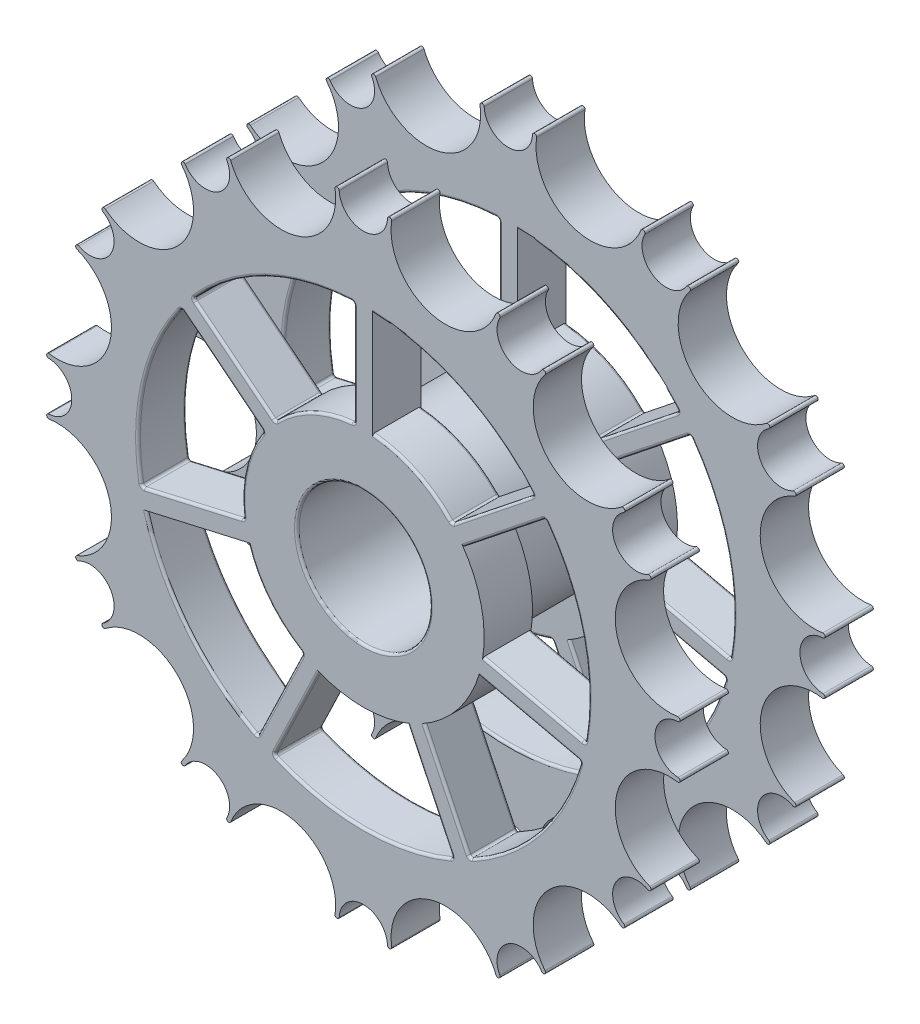
SolidWorks part; units mm, degrees
ref_plane "Front Plane" through (0, 0, 0) normal (0, 0, 1) x (1, 0, 0)
ref_plane "Top Plane" through (0, 0, 0) normal (0, 1, 0) x (1, 0, 0)
ref_plane "Right Plane" through (0, 0, 0) normal (1, 0, 0) x (0, 0, -1)
sketch "Sketch2" plane through (0, 0, 0) normal (0, 0, 1) x (1, 0, 0)
  line L0 (-169.1, 0) -> (169.1, 0) construction
  line L1 (169.1, 0) -> (0, 0) construction
  line L2 (-103.7648, 113.1639) -> (-169.1, 130.6704) construction
  line L3 (-234.4352, -113.1639) -> (-169.1, -130.6704) construction
  line L4 (-169.1, -130.6704) -> (-103.7648, -113.1639) construction
  line L5 (-103.7648, -113.1639) -> (-55.9361, -65.3352) construction
  line L6 (-55.9361, -65.3352) -> (-38.4296, 0) construction
  line L7 (-38.4296, 0) -> (-55.9361, 65.3352) construction
  line L8 (-55.9361, 65.3352) -> (-103.7648, 113.1639) construction
  line L9 (-169.1, 130.6704) -> (-234.4352, 113.1639) construction
  line L10 (-234.4352, 113.1639) -> (-282.2639, 65.3352) construction
  line L11 (-282.2639, 65.3352) -> (-299.7704, 0) construction
  line L12 (-299.7704, 0) -> (-282.2639, -65.3352) construction
  line L13 (-282.2639, -65.3352) -> (-234.4352, -113.1639) construction
  line L14 (-169.1, 130.6704) -> (169.1, 130.6704) construction
  line L15 (234.4352, -113.1639) -> (282.2639, -65.3352) construction
  line L16 (282.2639, -65.3352) -> (299.7704, 0) construction
  line L17 (299.7704, 0) -> (282.2639, 65.3352) construction
  line L18 (282.2639, 65.3352) -> (234.4352, 113.1639) construction
  line L19 (234.4352, 113.1639) -> (169.1, 130.6704) construction
  line L20 (169.1, 130.6704) -> (103.7648, 113.1639) construction
  line L21 (103.7648, 113.1639) -> (55.9361, 65.3352) construction
  line L22 (55.9361, 65.3352) -> (38.4296, 0) construction
  line L23 (38.4296, 0) -> (55.9361, -65.3352) construction
  line L24 (55.9361, -65.3352) -> (103.7648, -113.1639) construction
  line L25 (103.7648, -113.1639) -> (169.1, -130.6704) construction
  line L26 (169.1, -130.6704) -> (234.4352, -113.1639) construction
  line L27 (-169.1, -130.6704) -> (169.1, -130.6704) construction
  line L28 (-201.7676, 121.9172) -> (-203.0617, 126.7468) construction
  line L29 (-169.1, 130.6704) -> (-169.1, 0) construction
  line L30 (-169.1, 0) -> (-234.4352, 113.1639) construction
  circle A0 centre (-169.1, 0) radius 126.218 construction
  circle A1 centre (169.1, 0) radius 126.218 construction
  arc A2 (-169.1, 130.6704) -> (-169.1, -130.6704) centre (-169.1, 0) ccw construction
  arc A3 (169.1, 130.6704) -> (169.1, -130.6704) centre (169.1, 0) cw construction
  arc A4 (-179.0914, 130.2547) -> (-169.1, 120.6704) centre (-169.1, 130.6704) ccw
  arc A6 (-224.0026, 118.5171) -> (-180.8115, 130.0902) centre (-203.0617, 126.7468) ccw
  arc A7 (-179.0914, 130.2547) -> (-180.8115, 130.0902) centre (-179.9559, 130.2187) ccw
  arc A8 (-224.0026, 118.5171) -> (-225.5746, 117.7996) centre (-224.8079, 118.2006) ccw
  arc A9 (-229.4352, 104.5037) -> (-225.5746, 117.7996) centre (-234.4352, 113.1639) ccw
  arc A10 (-157.3885, 130.0902) -> (-114.1974, 118.5171) centre (-135.1383, 126.7468) ccw
  arc A11 (-112.6254, 117.7996) -> (-108.7648, 104.5037) centre (-103.7648, 113.1639) ccw
  arc A12 (-169.1, 120.6704) -> (-159.1086, 130.2547) centre (-169.1, 130.6704) ccw
  arc A13 (-157.3885, 130.0902) -> (-159.1086, 130.2547) centre (-158.2441, 130.2187) ccw
  arc A14 (-112.6254, 117.7996) -> (-114.1974, 118.5171) centre (-113.3921, 118.2006) ccw
  arc A15 (-93.9125, 106.8056) -> (-62.2944, 75.1875) centre (-76.3149, 92.7851) ccw
  arc A16 (-61.2918, 73.7801) -> (-64.5963, 60.3352) centre (-55.9361, 65.3352) ccw
  arc A17 (-108.7648, 104.5037) -> (-95.3199, 107.8082) centre (-103.7648, 113.1639) ccw
  arc A18 (-93.9125, 106.8056) -> (-95.3199, 107.8082) centre (-94.5892, 107.3448) ccw
  arc A19 (-61.2918, 73.7801) -> (-62.2944, 75.1875) centre (-61.7552, 74.5108) ccw
  arc A20 (-50.5829, 54.9026) -> (-39.0098, 11.7115) centre (-42.3532, 33.9617) ccw
  arc A21 (-38.8453, 9.9914) -> (-48.4296, 0) centre (-38.4296, 0) ccw
  arc A22 (-64.5963, 60.3352) -> (-51.3004, 56.4746) centre (-55.9361, 65.3352) ccw
  arc A23 (-50.5829, 54.9026) -> (-51.3004, 56.4746) centre (-50.8994, 55.7079) ccw
  arc A24 (-38.8453, 9.9914) -> (-39.0098, 11.7115) centre (-38.8813, 10.8559) ccw
  arc A25 (-39.0098, -11.7115) -> (-50.5829, -54.9026) centre (-42.3532, -33.9617) ccw
  arc A26 (-51.3004, -56.4746) -> (-64.5963, -60.3352) centre (-55.9361, -65.3352) ccw
  arc A27 (-48.4296, 0) -> (-38.8453, -9.9914) centre (-38.4296, 0) ccw
  arc A28 (-39.0098, -11.7115) -> (-38.8453, -9.9914) centre (-38.8813, -10.8559) ccw
  arc A29 (-51.3004, -56.4746) -> (-50.5829, -54.9026) centre (-50.8994, -55.7079) ccw
  arc A30 (-62.2944, -75.1875) -> (-93.9125, -106.8056) centre (-76.3149, -92.7851) ccw
  arc A31 (-95.3199, -107.8082) -> (-108.7648, -104.5037) centre (-103.7648, -113.1639) ccw
  arc A32 (-64.5963, -60.3352) -> (-61.2918, -73.7801) centre (-55.9361, -65.3352) ccw
  arc A33 (-62.2944, -75.1875) -> (-61.2918, -73.7801) centre (-61.7552, -74.5108) ccw
  arc A34 (-95.3199, -107.8082) -> (-93.9125, -106.8056) centre (-94.5892, -107.3448) ccw
  arc A35 (-114.1974, -118.5171) -> (-157.3885, -130.0902) centre (-135.1383, -126.7468) ccw
  arc A36 (-159.1086, -130.2547) -> (-169.1, -120.6704) centre (-169.1, -130.6704) ccw
  arc A37 (-108.7648, -104.5037) -> (-112.6254, -117.7996) centre (-103.7648, -113.1639) ccw
  arc A38 (-114.1974, -118.5171) -> (-112.6254, -117.7996) centre (-113.3921, -118.2006) ccw
  arc A39 (-159.1086, -130.2547) -> (-157.3885, -130.0902) centre (-158.2441, -130.2187) ccw
  arc A40 (-180.8115, -130.0902) -> (-224.0026, -118.5171) centre (-203.0617, -126.7468) ccw
  arc A41 (-225.5746, -117.7996) -> (-229.4352, -104.5037) centre (-234.4352, -113.1639) ccw
  arc A42 (-169.1, -120.6704) -> (-179.0914, -130.2547) centre (-169.1, -130.6704) ccw
  arc A43 (-180.8115, -130.0902) -> (-179.0914, -130.2547) centre (-179.9559, -130.2187) ccw
  arc A44 (-225.5746, -117.7996) -> (-224.0026, -118.5171) centre (-224.8079, -118.2006) ccw
  arc A45 (-244.2875, -106.8056) -> (-275.9056, -75.1875) centre (-261.8851, -92.7851) ccw
  arc A46 (-276.9082, -73.7801) -> (-273.6037, -60.3352) centre (-282.2639, -65.3352) ccw
  arc A47 (-229.4352, -104.5037) -> (-242.8801, -107.8082) centre (-234.4352, -113.1639) ccw
  arc A48 (-244.2875, -106.8056) -> (-242.8801, -107.8082) centre (-243.6108, -107.3448) ccw
  arc A49 (-276.9082, -73.7801) -> (-275.9056, -75.1875) centre (-276.4448, -74.5108) ccw
  arc A50 (-287.6171, -54.9026) -> (-299.1902, -11.7115) centre (-295.8468, -33.9617) ccw
  arc A51 (-299.3547, -9.9914) -> (-289.7704, 0) centre (-299.7704, 0) ccw
  arc A52 (-273.6037, -60.3352) -> (-286.8996, -56.4746) centre (-282.2639, -65.3352) ccw
  arc A53 (-287.6171, -54.9026) -> (-286.8996, -56.4746) centre (-287.3006, -55.7079) ccw
  arc A54 (-299.3547, -9.9914) -> (-299.1902, -11.7115) centre (-299.3187, -10.8559) ccw
  arc A55 (-299.1902, 11.7115) -> (-287.6171, 54.9026) centre (-295.8468, 33.9617) ccw
  arc A56 (-286.8996, 56.4746) -> (-273.6037, 60.3352) centre (-282.2639, 65.3352) ccw
  arc A57 (-289.7704, 0) -> (-299.3547, 9.9914) centre (-299.7704, 0) ccw
  arc A58 (-299.1902, 11.7115) -> (-299.3547, 9.9914) centre (-299.3187, 10.8559) ccw
  arc A59 (-286.8996, 56.4746) -> (-287.6171, 54.9026) centre (-287.3006, 55.7079) ccw
  arc A60 (-275.9056, 75.1875) -> (-244.2875, 106.8056) centre (-261.8851, 92.7851) ccw
  arc A61 (-242.8801, 107.8082) -> (-229.4352, 104.5037) centre (-234.4352, 113.1639) ccw
  arc A62 (-273.6037, 60.3352) -> (-276.9082, 73.7801) centre (-282.2639, 65.3352) ccw
  arc A63 (-275.9056, 75.1875) -> (-276.9082, 73.7801) centre (-276.4448, 74.5108) ccw
  arc A64 (-242.8801, 107.8082) -> (-244.2875, 106.8056) centre (-243.6108, 107.3448) ccw
  point P214 (-169.1, 0)
  dimension "D2" = 12
  dimension "D4" = 45
  dimension "D6" = 10
  dimension "D1" = 338.2
  dimension "D3" = 67.64
  dimension "D5" = 5
extrude "Boss-Extrude1" add sketch "Sketch2" against normal blind 20 contours A60 A64 A61 A9 A8 A6 A7 A4 A12 A13 A10 A14 A11 A17 A18 A15 A19 A16 A22 A23 A20 A24 A21 A27 A28 A25 A29 A26 A32 A33 A30 A34 A31 A37 A38 A35 A39 A36 A42 A43 A40 A44 A41 A47 A48 A45 A49 A46 A52 A53 A50 A54 A51 A57 A58 A55 A59 A56 A62 A63
sketch "Sketch3" plane through (0, 0, -20) normal (0, 0, -1) x (-1, 0, 0)
  line L0 (48.4296, 0) -> (289.7704, 0) construction
  line L1 (289.7704, 0) -> (169.1, 0) construction
  arc A0 (38.8453, -9.9914) -> (38.8453, 9.9914) centre (38.4296, 0) ccw construction
  arc A1 (299.3547, 9.9914) -> (299.3547, -9.9914) centre (299.7704, 0) ccw construction
  circle A2 centre (169.1, 0) radius 93.2915
extrude "Cut-Extrude1" cut sketch "Sketch3" against normal up to next
sketch "Sketch4" plane through (0, 0, 0) normal (0, 0, 1) x (1, 0, 0)
  line L0 (-169.1, 120.6704) -> (-169.1, -120.6704) construction
  arc A0 (-179.0914, 130.2547) -> (-159.1086, 130.2547) centre (-169.1, 130.6704) ccw construction
  arc A1 (-159.1086, -130.2547) -> (-179.0914, -130.2547) centre (-169.1, -130.6704) ccw construction
  circle A2 centre (-169.1, 0) radius 50
  dimension "D1" = 100
extrude "Boss-Extrude2" add sketch "Sketch4" against normal up to surface (20 mm away) separate body up to face at (-262.3915, 0, -20)
sketch "Sketch7" plane through (0, 0, -20) normal (0, 0, -1) x (-1, 0, 0)
  line L0 (169.1, 120.6704) -> (169.1, 50) construction
  line L1 (165.2724, 96.9149) -> (172.9276, 96.9149)
  line L2 (165.2724, 96.9149) -> (165.2724, 47.1267)
  line L3 (165.2724, 47.1267) -> (172.9276, 47.1267)
  line L4 (172.9276, 96.9149) -> (172.9276, 47.1267)
  arc A0 (159.1086, 130.2547) -> (179.0914, 130.2547) centre (169.1, 130.6704) ccw construction
  circle A1 centre (169.1, 0) radius 50 construction
extrude "Boss-Extrude3" add sketch "Sketch7" against normal up to surface (20 mm away) up to face at (-75.8085, 0, 0)
pattern_circular "CirPattern1" count 7 over 360 about axis through (-169.1, 0, 0) along (0, 0, 1) of "Boss-Extrude3"
sketch "Sketch8" plane through (0, 0, 0) normal (0, 0, 1) x (1, 0, 0)
  circle A0 centre (-169.1, 0) radius 27.5389
extrude "Cut-Extrude2" cut sketch "Sketch8" along direction (0, 0, 1) on the side against the normal up to next (20 mm away)
ref_plane "Plane1" through (0, 0, 20) normal (0, 0, 1) x (1, 0, 0)
mirror "Mirror11" about plane through (0, 0, 20) normal (0, 0, 1) of bodies 110
sketch "Sketch9" plane through (0, 0, 0) normal (0, 0, 1) x (1, 0, 0)
  circle A0 centre (-169.1, 0) radius 27.5389 construction
  circle A1 centre (-169.1, 0) radius 27.5389
  circle A2 centre (-169.1, 0) radius 37.5389
  dimension "D1" = 10
extrude "Boss-Extrude4" add sketch "Sketch9" along normal up to surface (40 mm away) up to face at (-141.5611, 0, 40)
fillet "Fillet2" radius 1 112 edges at (-128.6223, 84.0528, 0) (-128.6223, 84.0528, -20) (-172.9276, 93.213, -10) (-172.9276, 71.5331, -20) (-172.9276, 71.5331, 0) (-172.9276, 49.8533, -10) (-205.6904, 34.0755, -10) (-210.4633, 28.0905, -10) (-209.5777, 84.0528, -20) (-209.5777, 84.0528, 0) (-222.6404, 47.5927, -20) (-227.4133, 41.6077, -20) (-227.4133, 41.6077, 0) (-222.6404, 47.5927, 0) (-244.3633, 55.1248, -10) (-239.5904, 61.1098, -10) (-260.0525, 20.7593, 0) (-260.0525, 20.7593, -20) (-239.6914, -12.186, -20) (-237.9879, -19.6492, -20) (-237.9879, -19.6492, 0) (-239.6914, -12.186, 0) (-218.5551, -7.3618, -10) (-260.8276, -17.0102, -10) (-242.0383, -58.1663, 0) (-242.0383, -58.1663, -20) (-203.5856, -62.7884, -20) (-203.5856, -62.7884, 0) (-194.179, -43.2555, -10) (-212.9921, -82.3213, -10) (-169.1, -93.2915, 0) (-169.1, -93.2915, -20) (-141.5114, -66.1098, -20) (-134.6144, -62.7884, -20) (-134.6144, -62.7884, 0) (-141.5114, -66.1098, 0) (-125.2079, -82.3213, -10) (-132.1049, -85.6427, -10) (-96.1617, -58.1663, 0) (-96.1617, -58.1663, -20) (-100.2121, -19.6492, -20) (-98.5086, -12.186, -20) (-98.5086, -12.186, 0) (-100.2121, -19.6492, 0) (-77.3724, -17.0102, -10) (-79.0758, -24.4734, -10) (-78.1475, 20.7593, 0) (-78.1475, 20.7593, -20) (-110.7867, 41.6077, -20) (-115.5596, 47.5927, -20) (-132.5096, 34.0755, -10) (-115.5596, 47.5927, 0) (-110.7867, 41.6077, 0) (-98.6096, 61.1098, -10) (-93.8367, 55.1248, -10) (-141.5611, 0, -20) (-128.6223, 84.0528, 40) (-132.5096, 34.0755, 50) (-78.1475, 20.7593, 40) (-96.1617, -58.1663, 40) (-169.1, -93.2915, 40) (-242.0383, -58.1663, 40) (-194.179, -43.2555, 50) (-260.0525, 20.7593, 40) (-218.5551, -7.3618, 50) (-210.4633, 28.0905, 50) (-141.5611, 0, 60) (-78.1475, 20.7593, 60) (-128.6223, 84.0528, 60) (-96.1617, -58.1663, 60) (-169.1, -93.2915, 60) (-242.0383, -58.1663, 60) (-260.0525, 20.7593, 60) (-209.5777, 84.0528, 60) (-110.7867, 41.6077, 40) (-98.5086, -12.186, 40) (-115.5596, 47.5927, 40) (-100.2121, -19.6492, 40) (-134.6144, -62.7884, 40) (-141.5114, -66.1098, 40) (-196.6886, -66.1098, 40) (-203.5856, -62.7884, 40) (-239.6914, -12.186, 40) (-227.4133, 41.6077, 40) (-172.9276, 71.5331, 40) (-222.6404, 47.5927, 40) (-209.5777, 84.0528, 40) (-172.9276, 49.8533, 50) (-172.9276, 71.5331, 60) (-172.9276, 93.213, 50) (-205.6904, 34.0755, 50) (-244.3633, 55.1248, 50) (-227.4133, 41.6077, 60) (-239.5904, 61.1098, 50) (-222.6404, 47.5927, 60) (-260.8276, -17.0102, 50) (-239.6914, -12.186, 60) (-196.6886, -66.1098, 60) (-212.9921, -82.3213, 50) (-203.5856, -62.7884, 60) (-125.2079, -82.3213, 50) (-134.6144, -62.7884, 60) (-132.1049, -85.6427, 50) (-141.5114, -66.1098, 60) (-77.3724, -17.0102, 50) (-98.5086, -12.186, 60) (-79.0758, -24.4734, 50) (-100.2121, -19.6492, 60) (-98.6096, 61.1098, 50) (-115.5596, 47.5927, 60) (-93.8367, 55.1248, 50) (-110.7867, 41.6077, 60)
ref_plane "Plane2" through (0, 0, 20) normal (0, 0, 1) x (1, 0, 0)
ref_plane "Plane3" through (0, 0, 20) normal (0, 0, 1) x (1, 0, 0)
